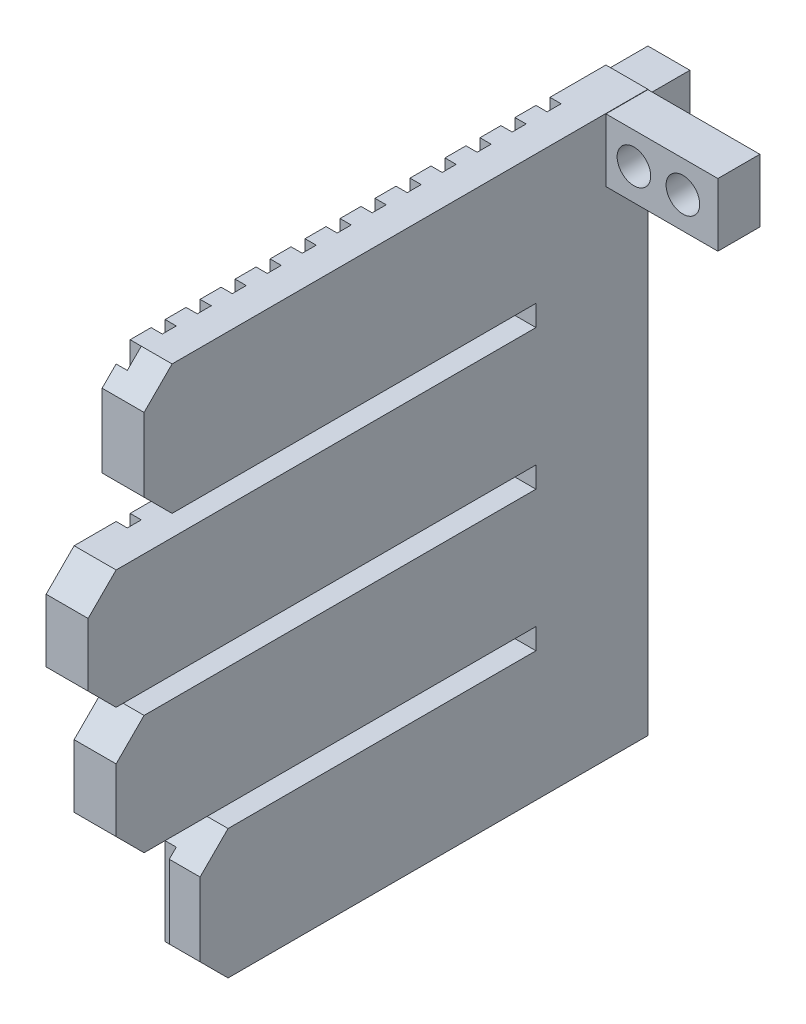
SolidWorks part; units mm, degrees
ref_plane "Front Plane" through (0, 0, 0) normal (0, 0, 1) x (1, 0, 0)
ref_plane "Top Plane" through (0, 0, 0) normal (0, 1, 0) x (1, 0, 0)
ref_plane "Right Plane" through (0, 0, 0) normal (1, 0, 0) x (0, 0, -1)
sketch "Sketch1" plane through (0, 0, 0) normal (0, 0, 1) x (1, 0, 0)
  line L0 (10, -20) -> (13, -20)
  line L1 (13, -20) -> (13, 20)
  line L2 (13, 20) -> (10, 20)
  line L3 (10, 20) -> (10, -20)
extrude "Boss-Extrude1" add sketch "Sketch1" along normal blind 8 from offset 25
sketch "Sketch2" plane through (0, 0, 0) normal (0, 0, 1) x (1, 0, 0)
  line L0 (10, 10.75) -> (13, 10.75)
  line L1 (13, 10.75) -> (13, 20)
  line L2 (13, 20) -> (10, 20)
  line L3 (10, 20) -> (10, 10.75)
  line L4 (10, 0.75) -> (13, 0.75)
  line L5 (13, 0.75) -> (13, 9.25)
  line L6 (13, 9.25) -> (10, 9.25)
  line L7 (10, 9.25) -> (10, 0.75)
  line L8 (10, -9.25) -> (13, -9.25)
  line L9 (13, -9.25) -> (13, -0.75)
  line L10 (13, -0.75) -> (10, -0.75)
  line L11 (10, -0.75) -> (10, -9.25)
  line L12 (10, -20) -> (13, -20)
  line L13 (13, -20) -> (13, -10.75)
  line L14 (13, -10.75) -> (10, -10.75)
  line L15 (10, -10.75) -> (10, -20)
extrude "Boss-Extrude2" add sketch "Sketch2" along normal blind 32.5 from offset 32.5
sketch "Sketch3" plane through (0, 0, 0) normal (0, 0, 1) x (1, 0, 0)
  line L0 (13, 15.475) -> (21, 15.475)
  line L1 (21, 15.475) -> (21, 19.975)
  line L2 (21, 19.975) -> (13, 19.975)
  line L3 (13, 19.975) -> (13, 15.475)
extrude "Boss-Extrude3" add sketch "Sketch3" along normal blind 3 from offset 25
sketch "Sketch4" plane through (0, 0, 0) normal (0, 0, 1) x (1, 0, 0)
  line L0 (10, 15.775) -> (13, 15.775)
  line L1 (13, 15.775) -> (13, 19.675)
  line L2 (13, 19.675) -> (10, 19.675)
  line L3 (10, 19.675) -> (10, 15.775)
extrude "Boss-Extrude4" add sketch "Sketch4" along normal blind 3 from offset 22
sketch "Sketch5" plane through (0, 0, 0) normal (0, 0, 1) x (1, 0, 0)
  circle A0 centre (15, 17.725) radius 1.2
  circle A1 centre (18.5, 17.725) radius 1.2
extrude "Cut-Extrude1" cut sketch "Sketch5" against normal through all and the other way through all
sketch "Sketch6" plane through (0, 0, 0) normal (0, 1, 0) x (1, 0, 0)
  line L0 (9, -29) -> (10.8, -29)
  line L1 (10.8, -29) -> (10.8, -30)
  line L2 (10.8, -30) -> (9, -30)
  line L3 (9, -30) -> (9, -29)
  line L4 (9, -31.5) -> (10.8, -31.5)
  line L5 (10.8, -31.5) -> (10.8, -32.5)
  line L6 (10.8, -32.5) -> (9, -32.5)
  line L7 (9, -32.5) -> (9, -31.5)
  line L8 (9, -34) -> (10.8, -34)
  line L9 (10.8, -34) -> (10.8, -35)
  line L10 (10.8, -35) -> (9, -35)
  line L11 (9, -35) -> (9, -34)
  line L12 (9, -36.5) -> (10.8, -36.5)
  line L13 (10.8, -36.5) -> (10.8, -37.5)
  line L14 (10.8, -37.5) -> (9, -37.5)
  line L15 (9, -37.5) -> (9, -36.5)
  line L16 (9, -39) -> (10.8, -39)
  line L17 (10.8, -39) -> (10.8, -40)
  line L18 (10.8, -40) -> (9, -40)
  line L19 (9, -40) -> (9, -39)
  line L20 (9, -41.5) -> (10.8, -41.5)
  line L21 (10.8, -41.5) -> (10.8, -42.5)
  line L22 (10.8, -42.5) -> (9, -42.5)
  line L23 (9, -42.5) -> (9, -41.5)
  line L24 (9, -44) -> (10.8, -44)
  line L25 (10.8, -44) -> (10.8, -45)
  line L26 (10.8, -45) -> (9, -45)
  line L27 (9, -45) -> (9, -44)
  line L28 (9, -46.5) -> (10.8, -46.5)
  line L29 (10.8, -46.5) -> (10.8, -47.5)
  line L30 (10.8, -47.5) -> (9, -47.5)
  line L31 (9, -47.5) -> (9, -46.5)
  line L32 (9, -49) -> (10.8, -49)
  line L33 (10.8, -49) -> (10.8, -50)
  line L34 (10.8, -50) -> (9, -50)
  line L35 (9, -50) -> (9, -49)
  line L36 (9, -51.5) -> (10.8, -51.5)
  line L37 (10.8, -51.5) -> (10.8, -52.5)
  line L38 (10.8, -52.5) -> (9, -52.5)
  line L39 (9, -52.5) -> (9, -51.5)
  line L40 (9, -54) -> (10.8, -54)
  line L41 (10.8, -54) -> (10.8, -55)
  line L42 (10.8, -55) -> (9, -55)
  line L43 (9, -55) -> (9, -54)
  line L44 (9, -56.5) -> (10.8, -56.5)
  line L45 (10.8, -56.5) -> (10.8, -57.5)
  line L46 (10.8, -57.5) -> (9, -57.5)
  line L47 (9, -57.5) -> (9, -56.5)
  line L48 (9, -59) -> (10.8, -59)
  line L49 (10.8, -59) -> (10.8, -60)
  line L50 (10.8, -60) -> (9, -60)
  line L51 (9, -60) -> (9, -59)
extrude "Cut-Extrude2" cut sketch "Sketch6" against normal through all and the other way through all
sketch "Sketch7" plane through (0, 0, 0) normal (1, 0, 0) x (0, 0, -1)
  line L0 (-61, 10.05) -> (-61, 20.7)
  line L1 (-61, 20.7) -> (-70, 20.7)
  line L2 (-70, 20.7) -> (-70, 10.05)
  line L3 (-70, 10.05) -> (-61, 10.05)
  line L4 (-63, -9.95) -> (-63, -0.05)
  line L5 (-63, -0.05) -> (-70, -0.05)
  line L6 (-70, -0.05) -> (-70, -9.95)
  line L7 (-70, -9.95) -> (-63, -9.95)
  line L8 (-57, -20.7) -> (-57, -10.05)
  line L9 (-57, -10.05) -> (-70, -10.05)
  line L10 (-70, -10.05) -> (-70, -20.7)
  line L11 (-70, -20.7) -> (-57, -20.7)
extrude "Cut-Extrude3" cut sketch "Sketch7" against normal through all and the other way through all
sketch "Sketch8" plane through (0, 0, 0) normal (1, 0, 0) x (0, 0, -1)
  line L0 (-58.3, 10.05) -> (-62, 10.05)
  line L1 (-62, 10.05) -> (-62, 13.75)
  line L2 (-62, 13.75) -> (-58.3, 10.05)
  line L3 (-58.3, 20.7) -> (-62, 17)
  line L4 (-62, 17) -> (-62, 20.7)
  line L5 (-62, 20.7) -> (-58.3, 20.7)
  line L6 (-62.3, 0.05) -> (-66, 0.05)
  line L7 (-66, 0.05) -> (-66, 3.75)
  line L8 (-66, 3.75) -> (-62.3, 0.05)
  line L9 (-62.3, 9.95) -> (-66, 6.25)
  line L10 (-66, 6.25) -> (-66, 9.95)
  line L11 (-66, 9.95) -> (-62.3, 9.95)
  line L12 (-60.3, -9.95) -> (-64, -9.95)
  line L13 (-64, -9.95) -> (-64, -6.25)
  line L14 (-64, -6.25) -> (-60.3, -9.95)
  line L15 (-60.3, -0.05) -> (-64, -3.75)
  line L16 (-64, -3.75) -> (-64, -0.05)
  line L17 (-64, -0.05) -> (-60.3, -0.05)
  line L18 (-54.3, -20.7) -> (-58, -20.7)
  line L19 (-58, -20.7) -> (-58, -17)
  line L20 (-58, -17) -> (-54.3, -20.7)
  line L21 (-54.3, -10.05) -> (-58, -13.75)
  line L22 (-58, -13.75) -> (-58, -10.05)
  line L23 (-58, -10.05) -> (-54.3, -10.05)
extrude "Cut-Extrude4" cut sketch "Sketch8" against normal through all and the other way through all
